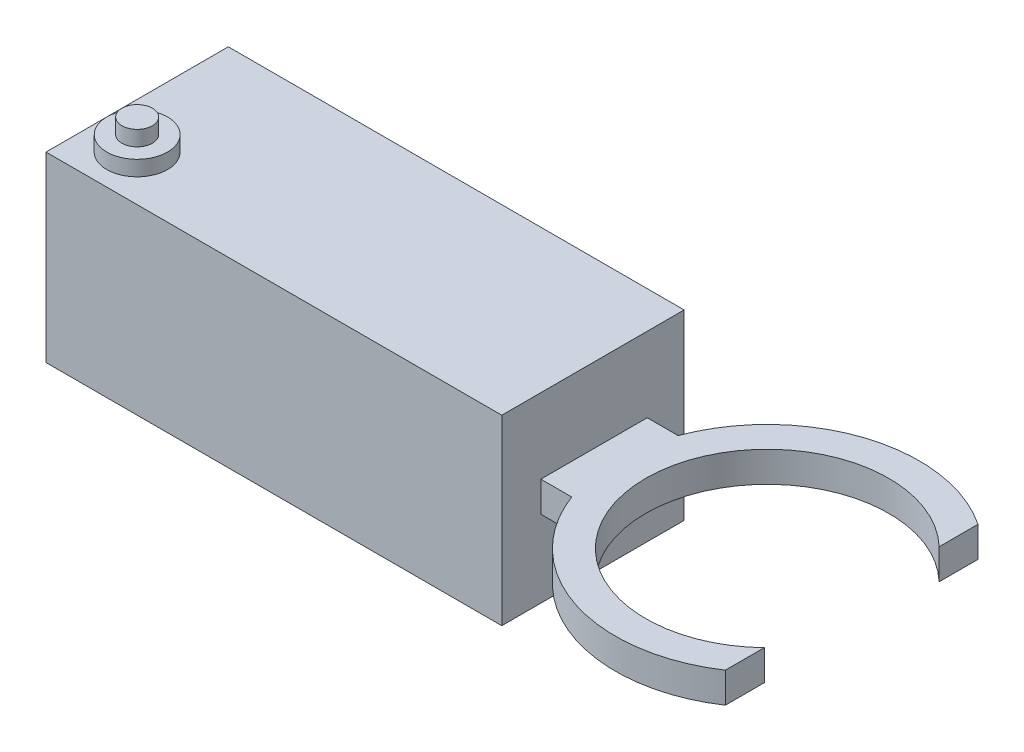
SolidWorks part; units mm, degrees
ref_plane "Front Plane" through (0, 0, 0) normal (0, 0, 1) x (1, 0, 0)
ref_plane "Top Plane" through (0, 0, 0) normal (0, 1, 0) x (1, 0, 0)
ref_plane "Right Plane" through (0, 0, 0) normal (1, 0, 0) x (0, 0, -1)
sketch "Sketch1" plane through (0, 0, 0) normal (0, 0, 1) x (1, 0, 0)
  line L1 (75, 30) -> (-75, 30)
  line L2 (75, 30) -> (75, -30)
  line L3 (75, -30) -> (-75, -30)
  line L4 (-75, 30) -> (-75, -30)
  line L5 (75, 30) -> (-75, -30) construction
  line L6 (75, -30) -> (-75, 30) construction
  point P0 (0, 0)
  dimension "D1" = 150
  dimension "D2" = 60
extrude "Boss-Extrude2" add sketch "Sketch1" against normal blind 60
sketch "Sketch3" plane through (0, 30, 0) normal (0, 1, 0) x (1, 0, 0)
  line L0 (-75, 60) -> (-75, 0) construction
  line L1 (75, 0) -> (-75, 0) construction
  circle A0 centre (-60, 15) radius 10
  dimension "D1" = 20
  dimension "D2" = 15
  dimension "D3" = 15
extrude "Boss-Extrude3" add sketch "Sketch3" along normal blind 5
sketch "Sketch4" plane through (0, 35, 0) normal (0, 1, 0) x (1, 0, 0)
  circle A0 centre (-60, 15) radius 5
  dimension "D1" = 10
extrude "Boss-Extrude4" add sketch "Sketch4" along normal blind 5
sketch "Sketch5" plane through (75, 0, 0) normal (1, 0, 0) x (0, 0, -1)
  line L0 (60, -30) -> (60, 30) construction
  line L1 (47.8619, 5.3404) -> (12.8619, 5.3404)
  line L2 (47.8619, 5.3404) -> (47.8619, -4.6596)
  line L3 (47.8619, -4.6596) -> (12.8619, -4.6596)
  line L4 (12.8619, 5.3404) -> (12.8619, -4.6596)
  point P0 (30, 0)
  dimension "D1" = 30
  dimension "D2" = 10
  dimension "D3" = 35
extrude "Boss-Extrude5" add sketch "Sketch5" along normal blind 15
sketch "Sketch6" plane through (0, 5.3404, 0) normal (0, 1, 0) x (1, 0, 0)
  line L0 (159.7901, 1.592) -> (159.7901, -11.2038)
  line L2 (90, 47.8619) -> (90, 12.8619) construction
  line L3 (159.7901, 71.9276) -> (159.7901, 59.1319)
  arc A0 (159.7901, 71.9276) -> (159.7901, -11.2038) centre (132, 30.3619) ccw
  arc A1 (159.7901, 59.1319) -> (159.7901, 1.592) centre (132, 30.3619) ccw
  point P2 (90, 30.3619)
  point P3 (92, 30.3619)
  dimension "D1" = 100
  dimension "D2" = 80
  dimension "D3" = 2
extrude "Boss-Extrude7" add sketch "Sketch6" against normal blind 10
